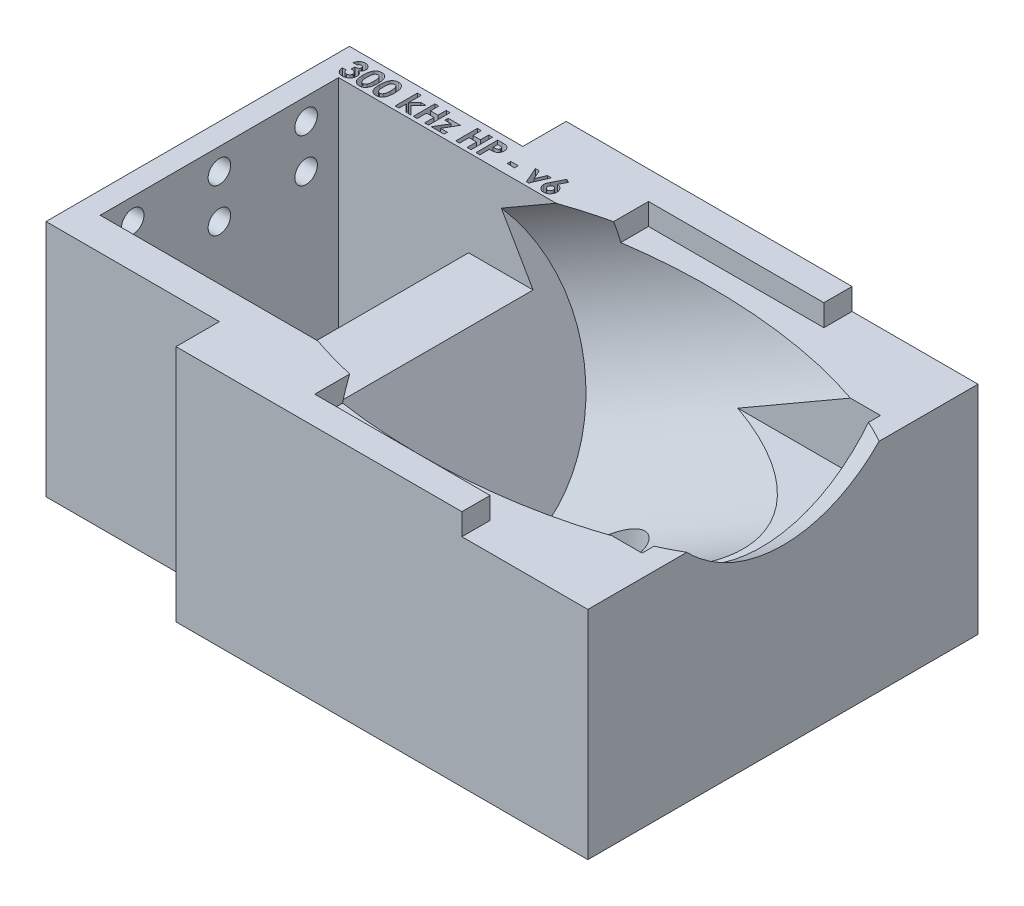
SolidWorks part; units mm, degrees
ref_plane "Front Plane" through (0, 0, 0) normal (0, 0, 1) x (1, 0, 0)
ref_plane "Top Plane" through (0, 0, 0) normal (0, 1, 0) x (1, 0, 0)
ref_plane "Right Plane" through (0, 0, 0) normal (1, 0, 0) x (0, 0, -1)
sketch "Sketch1" plane through (0, 0, 0) normal (0, 0, 1) x (1, 0, 0)
  line L1 (-139.7, -127) -> (88.9, -127)
  line L2 (-139.7, -127) -> (-139.7, 0)
  line L3 (-139.7, 0) -> (88.9, 0)
  line L4 (88.9, -127) -> (88.9, 0)
  line L5 (-139.7, -127) -> (88.9, 0) construction
  line L6 (-139.7, 0) -> (88.9, -127) construction
  point P0 (0, 0)
  dimension "D1" = 228.6
  dimension "D2" = 127
  dimension "D3" = 88.9
extrude "Boss-Extrude1" add sketch "Sketch1" along normal mid plane 101.6
sketch "Sketch10" plane through (0, -127, 0) normal (0, -1, 0) x (1, 0, 0)
  circle A0 centre (0, 0) radius 12.7
  dimension "D1" = 25.4
extrude "Cut-Extrude6" cut sketch "Sketch10" against normal through all
sketch "Sketch2" plane through (0, 0, 0) normal (0, 0, 1) x (1, 0, 0)
  line L0 (-48.125, -30.325) -> (0, -2.54) construction
  line L1 (0, 46.5867) -> (-47.9201, 18.9201)
  line L2 (-50.1425, -26.8306) -> (-69.3975, 6.5201)
  line L3 (-69.3975, 6.5201) -> (-47.9201, 18.9201)
  line L4 (-50.1425, -26.8306) -> (-48.125, -30.325)
  line L5 (-26.6476, -17.925) -> (-47.9201, 18.9201) construction
  line L7 (0, -2.54) -> (87.9882, 48.26)
  line L8 (-83.8, -2.54) -> (0, -2.54) construction
  line L10 (0, -2.54) -> (-48.125, -30.325)
  line L11 (88.9, 0) -> (-139.7, 0) construction
  line L12 (87.9882, 48.26) -> (66.7157, 85.1051)
  line L13 (0, 46.5867) -> (0, -2.54) construction
  line L17 (66.7157, 85.1051) -> (0, 46.5867)
  point P23 (-26.6476, -17.925)
  dimension "D1" = 30
  dimension "D2" = 24.8
  dimension "D3" = 2.54
  dimension "D4" = 30.77
  dimension "D5" = 42.545
  dimension "D6" = 101.6
revolve "Cut-Revolve1" cut sketch "Sketch2" angle 360 about L0
sketch "Sketch11" plane through (0, -127, 0) normal (0, -1, 0) x (1, 0, 0)
  line L1 (13, 13) -> (-13, 13)
  line L2 (13, 13) -> (13, -13)
  line L3 (13, -13) -> (-13, -13)
  line L4 (-13, 13) -> (-13, -13)
  line L5 (13, 13) -> (-13, -13) construction
  line L6 (13, -13) -> (-13, 13) construction
  point P0 (0, 0)
  dimension "D1" = 26
sketch "Sketch22" plane through (0, 0, 0) normal (0, 1, 0) x (1, 0, 0)
  line L0 (88.9, -50.8) -> (-139.7, -50.8) construction
  line L1 (-139.7, 50.8) -> (-114.3, 50.8)
  line L2 (-139.7, 50.8) -> (-139.7, -50.8)
  line L3 (-139.7, -50.8) -> (-114.3, -50.8)
  line L4 (-114.3, 50.8) -> (-114.3, -50.8)
  dimension "D1" = 25.4
extrude "Cut-Extrude17" cut sketch "Sketch22" against normal through all
sketch "Sketch23" plane through (0, -127, 0) normal (0, -1, 0) x (1, 0, 0)
  line L0 (-127, 127) -> (127, -127) construction
  line L1 (-127, 127) -> (127, 127)
  line L2 (-127, 127) -> (-127, -127)
  line L3 (-127, -127) -> (127, -127)
  line L4 (127, 127) -> (127, -127)
  dimension "D1" = 254
  dimension "D2" = 254
extrude "Cut-Extrude18" cut sketch "Sketch23" against normal blind 57.15
sketch "Sketch21" plane through (0, 0, 0) normal (0, 1, 0) x (1, 0, 0)
  line L1 (88.9, -50.8) -> (57.15, -50.8)
  line L2 (88.9, -50.8) -> (88.9, 50.8)
  line L3 (88.9, 50.8) -> (57.15, 50.8)
  line L4 (57.15, -50.8) -> (57.15, 50.8)
  line L5 (88.9, -50.8) -> (-114.3, -50.8) construction
  line L6 (88.9, 50.8) -> (-114.3, 50.8) construction
  line L7 (-114.3, -50.8) -> (-114.3, 50.8) construction
  dimension "D1" = 171.45
extrude "Cut-Extrude16" cut sketch "Sketch21" against normal through all
sketch "Sketch26" plane through (0, 0, 0) normal (0, 1, 0) x (1, 0, 0)
  line L0 (57.15, 50.8) -> (57.15, 33.3829) construction
  line L1 (-107.95, -34.925) -> (50.8, -34.925)
  line L2 (-107.95, -34.925) -> (-107.95, 34.925)
  line L3 (-107.95, 34.925) -> (50.8, 34.925)
  line L4 (50.8, -34.925) -> (50.8, 34.925)
  line L5 (-114.3, -50.8) -> (-114.3, 50.8) construction
  point P4 (-107.95, 0)
  dimension "D1" = 6.35
  dimension "D2" = 6.35
  dimension "D3" = 69.85
extrude "Cut-Extrude21" cut sketch "Sketch26" against normal blind 25.4
sketch "Sketch27" plane through (-114.3, 0, 0) normal (-1, 0, 0) x (0, 0, 1)
  line L0 (50.8, 0) -> (-50.8, 0) construction
  line L1 (-25.4, -6.35) -> (25.4, -6.35) construction
  line L2 (-25.4, -6.35) -> (-25.4, -19.05) construction
  line L3 (-25.4, -19.05) -> (25.4, -19.05) construction
  line L4 (25.4, -6.35) -> (25.4, -19.05) construction
  line L7 (-25.4, -19.05) -> (-25.4, -31.75) construction
  line L8 (-25.4, -31.75) -> (25.4, -31.75) construction
  line L9 (25.4, -19.05) -> (25.4, -31.75) construction
  circle A0 centre (-25.4, -6.35) radius 3.302
  circle A1 centre (0, -6.35) radius 3.302
  circle A2 centre (0, -19.05) radius 3.302
  circle A3 centre (25.4, -6.35) radius 3.302
  circle A4 centre (25.4, -19.05) radius 3.302
  circle A5 centre (-25.4, -19.05) radius 3.302
  circle A7 centre (-25.4, -31.75) radius 3.302 [skipped]
  circle A8 centre (0, -31.75) radius 3.302 [skipped]
  circle A9 centre (25.4, -31.75) radius 3.302 [skipped]
  point P4 (0, -6.35)
  dimension "D5" = 6.604
  dimension "D8" = 25.4
  dimension "D1" = 50.8
  dimension "D2" = 12.7
  dimension "D3" = 6.35
  dimension "D4" = 12.7
  dimension "D6" = 3
  dimension "D7" = 3
extrude "Cut-Extrude22" cut sketch "Sketch27" against normal up to next and the other way through all
sketch "Sketch28" plane through (0, 0, 0) normal (0, 1, 0) x (1, 0, 0)
  line L0 (-114.3, 36.0198) -> (-43.5568, 36.0198) construction
  line L3 (-114.3, -50.8) -> (-114.3, 50.8) construction
  text T0 "<b>300 kHz HP - v6</b>" font "Century Gothic" height 6.35
extrude "Cut-Extrude23" cut sketch "Sketch28" against normal blind 3.175
sketch "Sketch30" plane through (0, -25.4, 0) normal (0, 1, 0) x (1, 0, 0)
  circle A0 centre (-95.25, 25.4) radius 3.429
  circle A2 centre (-82.55, 25.4) radius 3.429
  circle A3 centre (-82.55, 12.7) radius 3.429
  circle A4 centre (-82.55, 0) radius 3.429
  circle A5 centre (-82.55, -12.7) radius 3.429
  circle A6 centre (-82.55, -25.4) radius 3.429
  circle A7 centre (-95.25, 12.7) radius 3.429
  circle A8 centre (-95.25, 0) radius 3.429
  circle A9 centre (-95.25, -12.7) radius 3.429
  circle A10 centre (-95.25, -25.4) radius 3.429
  dimension "D1" = 6.858
  dimension "D2" = 25.4
  dimension "D3" = 95.25
  dimension "D4" = 2
  dimension "D5" = 5
extrude "Cut-Extrude24" cut sketch "Sketch30" against normal through all
sketch "Sketch31" plane through (0, -25.4, 0) normal (0, 1, 0) x (1, 0, 0)
  line L0 (-107.95, -34.925) -> (-44.1937, -34.925) construction
  line L1 (-107.95, 34.925) -> (-69.85, 34.925)
  line L2 (-107.95, 34.925) -> (-107.95, -34.925)
  line L3 (-107.95, -34.925) -> (-69.85, -34.925)
  line L4 (-69.85, 34.925) -> (-69.85, -34.925)
  dimension "D1" = 38.1
extrude "Cut-Extrude25" cut sketch "Sketch31" against normal offset from surface (38.1 mm away) 6.35 up to face at (-82.55, -69.85, 28.829)
sketch "Sketch32" plane through (0, 0, 0) normal (0, 1, 0) x (1, 0, 0)
  line L0 (57.15, 50.8) -> (57.15, 33.3829) construction
  line L1 (-31.1262, 48.895) -> (57.15, 48.895)
  line L2 (-31.1262, 48.895) -> (-31.1262, -48.895)
  line L3 (-31.1262, -48.895) -> (57.15, -48.895)
  line L4 (57.15, 48.895) -> (57.15, -48.895)
  point P4 (57.15, 0)
  dimension "D1" = 97.79
extrude "Cut-Extrude26" cut sketch "Sketch32" against normal blind 6.35
sketch "Sketch33" plane through (0, 0, 0) normal (0, 1, 0) x (1, 0, 0)
  line L1 (57.15, 50.8) -> (20.2503, 50.8)
  line L2 (57.15, 50.8) -> (57.15, -50.8)
  line L3 (57.15, -50.8) -> (20.2503, -50.8)
  line L4 (20.2503, 50.8) -> (20.2503, -50.8)
  line L5 (57.15, -50.8) -> (-114.3, -50.8) construction
extrude "Cut-Extrude27" cut sketch "Sketch33" against normal blind 6.35
sketch "Sketch34" plane through (0, 0, 50.8) normal (0, 0, 1) x (1, 0, 0)
  line L6 (57.15, -6.35) -> (20.2503, -6.35)
  line L7 (20.2503, -6.35) -> (20.2503, 0)
  line L8 (20.2503, 0) -> (-114.3, 0)
  line L9 (-114.3, 0) -> (-114.3, -69.85)
  line L10 (-114.3, -69.85) -> (57.15, -69.85)
  line L11 (57.15, -69.85) -> (57.15, -6.35)
  line L12 (57.15, -6.35) -> (20.2503, -6.35)
  line L13 (20.2503, -6.35) -> (20.2503, 0)
  line L14 (20.2503, 0) -> (-114.3, 0)
  line L15 (-114.3, 0) -> (-114.3, -69.85)
  line L16 (-114.3, -69.85) -> (57.15, -69.85)
  line L17 (57.15, -69.85) -> (57.15, -6.35)
  dimension "D1" = 0
extrude "Boss-Extrude2" add sketch "Sketch34" along normal blind 6.35
sketch "Sketch35" plane through (0, 0, -50.8) normal (0, 0, -1) x (-1, 0, 0)
  line L6 (-20.2503, 0) -> (-20.2503, -6.35)
  line L7 (-20.2503, -6.35) -> (-57.15, -6.35)
  line L8 (-57.15, -6.35) -> (-57.15, -69.85)
  line L9 (-57.15, -69.85) -> (114.3, -69.85)
  line L10 (114.3, -69.85) -> (114.3, 0)
  line L11 (114.3, 0) -> (-20.2503, 0)
  line L12 (-20.2503, 0) -> (-20.2503, -6.35)
  line L13 (-20.2503, -6.35) -> (-57.15, -6.35)
  line L14 (-57.15, -6.35) -> (-57.15, -69.85)
  line L15 (-57.15, -69.85) -> (114.3, -69.85)
  line L16 (114.3, -69.85) -> (114.3, 0)
  line L17 (114.3, 0) -> (-20.2503, 0)
  dimension "D1" = 0
extrude "Boss-Extrude3" add sketch "Sketch35" along normal blind 6.35
sketch "Sketch36" plane through (0, 0, 0) normal (0, 1, 0) x (1, 0, 0)
  line L0 (-114.3, -57.15) -> (-114.3, 57.15) construction
  line L1 (-114.3, 57.15) -> (-63.5, 57.15)
  line L2 (-114.3, 57.15) -> (-114.3, 44.45)
  line L3 (-114.3, 44.45) -> (-63.5, 44.45)
  line L4 (-63.5, 57.15) -> (-63.5, 44.45)
  line L5 (-114.3, -57.15) -> (-63.5, -57.15)
  line L6 (-114.3, -57.15) -> (-114.3, -44.45)
  line L7 (-114.3, -44.45) -> (-63.5, -44.45)
  line L8 (-63.5, -57.15) -> (-63.5, -44.45)
  dimension "D1" = 50.8
  dimension "D2" = 12.7
extrude "Cut-Extrude28" cut sketch "Sketch36" against normal through all
